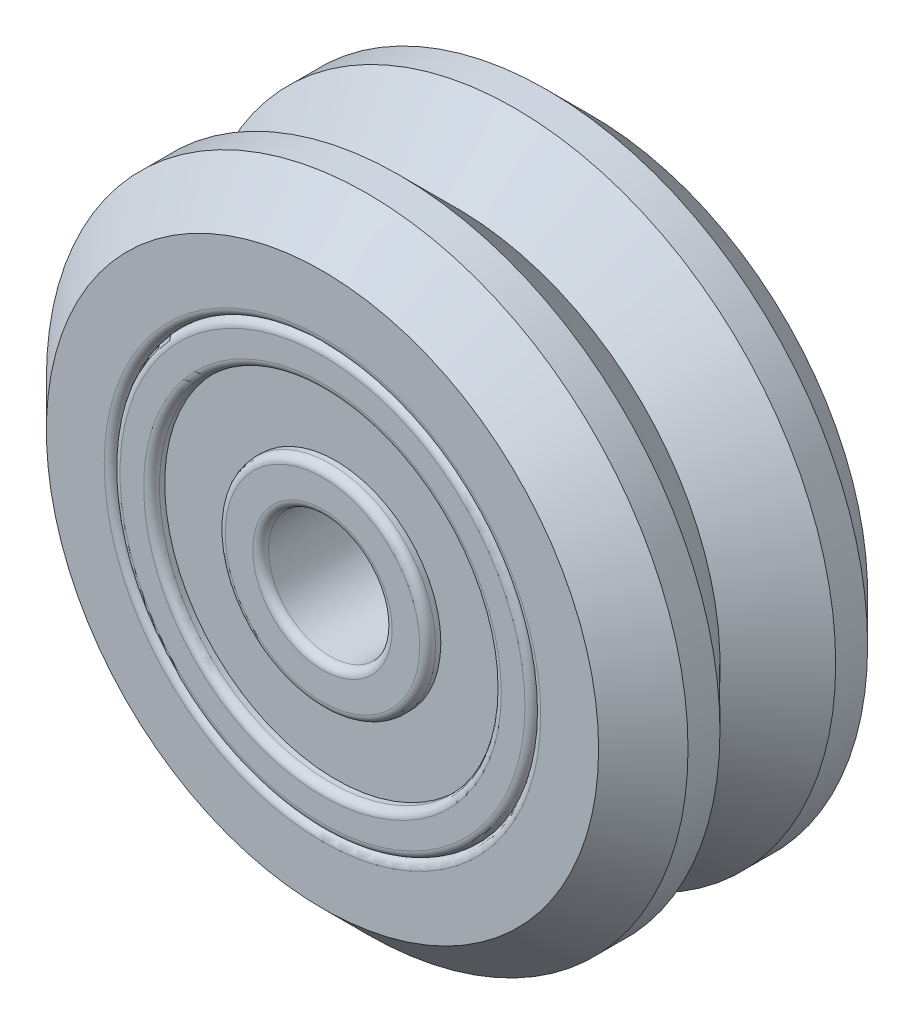
SolidWorks part; units mm, degrees
other "Ролик"
other "Подшипник 2"
other "Подшипник"
material "ABS"
ref_plane "Спереди" through (0, 0, 0) normal (0, 0, 1) x (1, 0, 0)
ref_plane "Сверху" through (0, 0, 0) normal (0, 1, 0) x (1, 0, 0)
ref_plane "Справа" through (0, 0, 0) normal (1, 0, 0) x (0, 0, -1)
sketch "Эскиз1" plane through (0, 0, 0) normal (0, 0, 1) x (1, 0, 0)
  circle A0 centre (0, 0) radius 12.2
  circle A1 centre (0, 0) radius 7
  dimension "D1" = 24.4
  dimension "D2" = 14
extrude "Бобышка-Вытянуть1" add sketch "Эскиз1" along normal blind 10.23
sketch "Эскиз2" plane through (0, 0, 10.23) normal (0, 0, 1) x (1, 0, 0)
  circle A2 centre (0, 0) radius 10.5
  dimension "D1" = 21
extrude "Вырез-Вытянуть1" cut sketch "Эскиз2" against normal blind 2.42 draft 45 flip side to cut
sketch "Эскиз4" plane through (0, 0, 0) normal (0, 0, -1) x (-1, 0, 0)
  circle A1 centre (0, 0) radius 10.5 construction
  circle A2 centre (0, 0) radius 10.5
extrude "Вырез-Вытянуть2" cut sketch "Эскиз4" against normal blind 2.42 draft 45 flip side to cut
sketch "Эскиз8" plane through (0, 0, 10.23) normal (0, 0, 1) x (1, 0, 0)
  circle A0 centre (0, 0) radius 8
  dimension "D1" = 16
extrude "Вырез-Вытянуть6" cut sketch "Эскиз8" against normal blind 4.615
sketch "Эскиз9" plane through (0, 0, 0) normal (0, 0, -1) x (-1, 0, 0)
  circle A0 centre (0, 0) radius 8 construction
  circle A1 centre (0, 0) radius 8
extrude "Вырез-Вытянуть7" cut sketch "Эскиз9" against normal blind 4.615
ref_plane "Плоскость1" through (0, 0, 5.115) normal (0, 0, -1) x (-1, 0, 0)
sketch "Эскиз7" plane through (0, 0, 5.115) normal (0, 0, -1) x (-1, 0, 0)
  circle A1 centre (0, 0) radius 10
  dimension "D1" = 20
extrude "Вырез-Вытянуть5" cut sketch "Эскиз7" along normal blind 2.695 draft 45 and the other way blind 2.695 draft 45 flip side to cut
fillet "Скругление1" radius 0.3 2 edges at (8, 0, 10.23) (-8, 0, 0)
sketch "Эскиз10" plane through (0, 0, 10.23) normal (0, 0, 1) x (1, 0, 0)
  circle A0 centre (0, 0) radius 8 construction
  circle A1 centre (0, 0) radius 8
  circle A2 centre (0, 0) radius 2.35
  dimension "D1" = 4.7
extrude "Бобышка-Вытянуть2" add sketch "Эскиз10" against normal blind 4.615 separate body
sketch "Эскиз11" plane through (0, 0, 10.23) normal (0, 0, 1) x (1, 0, 0)
  circle A0 centre (0, 0) radius 6.5
  circle A1 centre (0, 0) radius 4
  dimension "D1" = 13
  dimension "D2" = 8
extrude "Вырез-Вытянуть8" cut sketch "Эскиз11" against normal blind 0.5
fillet "Скругление2" radius 0.3 4 edges at (6.5, 0, 10.23) (8, 0, 10.23) (4, 0, 10.23) (2.35, 0, 10.23)
mirror "Зеркальное отражение1" about plane through (0, 0, 5.115) normal (0, 0, -1) of bodies 114
sketch "Sketch1" plane through (0, 0, 0) normal (0, 1, 0) x (1, 0, 0)
  line L0 (0, 8) -> (0, -8) construction
  line L1 (0, -5.115) -> (22, -5.115) construction
  line L3 (-10, -5.115) -> (10, -5.115) construction
  point P4 (0, 0)
  dimension "D1" = 8
  dimension "D2" = 22
